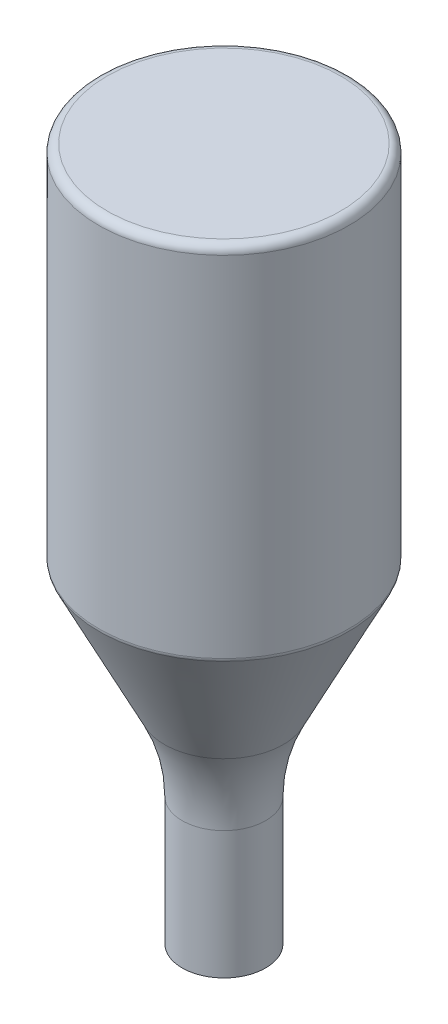
SolidWorks part; units mm, degrees
ref_plane "Plan de face" through (0, 0, 0) normal (0, 0, 1) x (1, 0, 0)
ref_plane "Plan de dessus" through (0, 0, 0) normal (0, 1, 0) x (1, 0, 0)
ref_plane "Plan de droite" through (0, 0, 0) normal (1, 0, 0) x (0, 0, -1)
sketch "Esquisse1" plane through (0, 0, 0) normal (0, 0, 1) x (1, 0, 0)
  line L0 (0, 0) -> (0, -200) construction
  line L1 (0, 0) -> (28, 0)
  line L2 (30, -2) -> (30, -119.6274)
  line L3 (29.8334, -120.3332) -> (14.2229, -151.5542)
  line L4 (10, -169.4427) -> (10, -200)
  line L5 (10, -200) -> (5, -200)
  line L6 (5, -200) -> (5, -170)
  line L7 (5, -170) -> (0, -170)
  line L8 (0, -170) -> (0, 0)
  arc A0 (30, -119.6274) -> (29.8334, -120.3332) centre (28.4218, -119.6274) cw
  arc A1 (14.2229, -151.5542) -> (10, -169.4427) centre (50, -169.4427) ccw
  arc A2 (28, 0) -> (30, -2) centre (28, -2) cw
  point P9 (30, -120)
  point P12 (10, -160)
  point P15 (30, 0)
  dimension "D8" = 2
  dimension "D1" = 200
  dimension "D3" = 120
  dimension "D4" = 30
  dimension "D9" = 5
  dimension "D10" = 20
revolve "Révolution1" add sketch "Esquisse1" angle 360 about L0
ref_plane "Plan1" through (50, 0, 0) normal (1, 0, 0) x (0, 0, -1)
sketch "Sketch1" plane through (0, 0, 0) normal (0, 1, 0) x (1, 0, 0)
  circle A0 centre (0, 0) radius 30.5918
extrude "Cut-Extrude1" cut sketch "Sketch1" against normal blind 34
fillet "Fillet1" radius 2 1 edges at (-30, -34, 0)
